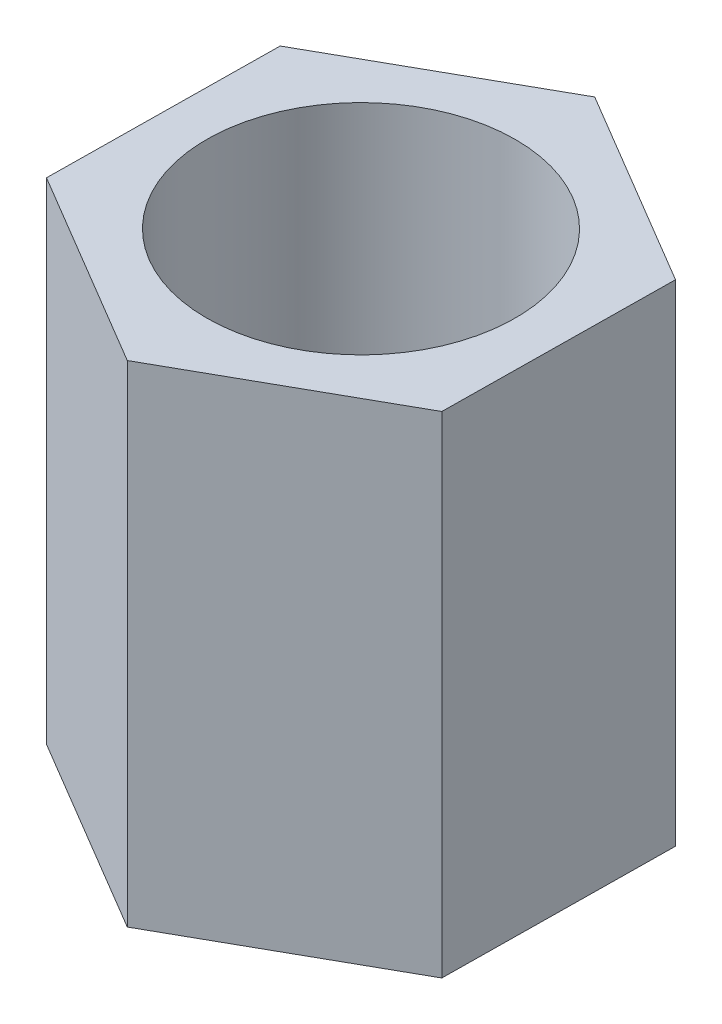
SolidWorks part; units mm, degrees
ref_plane "Front Plane" through (0, 0, 0) normal (0, 0, 1) x (1, 0, 0)
ref_plane "Top Plane" through (0, 0, 0) normal (0, 1, 0) x (1, 0, 0)
ref_plane "Right Plane" through (0, 0, 0) normal (1, 0, 0) x (0, 0, -1)
sketch "Sketch1" plane through (0, 0, 0) normal (0, 1, 0) x (1, 0, 0)
  line L1 (2.0247, -1.2011) -> (2.0525, 1.1529)
  line L2 (2.0525, 1.1529) -> (0.0278, 2.354)
  line L3 (0.0278, 2.354) -> (-2.0247, 1.2011)
  line L4 (-2.0247, 1.2011) -> (-2.0525, -1.1529)
  line L5 (-2.0525, -1.1529) -> (-0.0278, -2.354)
  line L6 (-0.0278, -2.354) -> (2.0247, -1.2011)
  circle A0 centre (0, 0) radius 1.575
  circle A1 centre (0, 0) radius 2.0387 construction
extrude "Boss-Extrude1" add sketch "Sketch1" along normal blind 5
